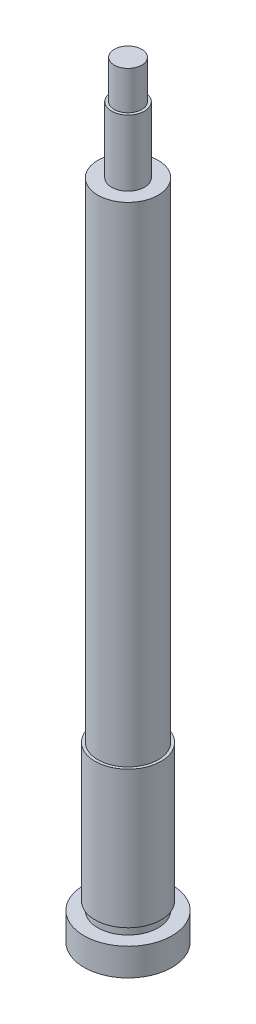
SolidWorks part; units mm, degrees
ref_plane "Front Plane" through (0, 0, 0) normal (0, 0, 1) x (1, 0, 0)
ref_plane "Top Plane" through (0, 0, 0) normal (0, 1, 0) x (1, 0, 0)
ref_plane "Right Plane" through (0, 0, 0) normal (1, 0, 0) x (0, 0, -1)
sketch "Sketch1" plane through (0, 0, 0) normal (0, 0, 1) x (1, 0, 0)
  line L0 (0, 0) -> (0, 279) construction
  line L1 (0, 0) -> (-16, 0)
  line L2 (-16, 0) -> (-16, 10)
  line L3 (0, 0) -> (0, 279)
  line L4 (-11, 63) -> (-11, 241)
  line L5 (-11, 10) -> (-16, 10)
  line L6 (-11, 13) -> (-12, 13)
  line L7 (-12, 13) -> (-12, 63)
  line L8 (-11, 10) -> (-11, 13)
  line L9 (-11, 63) -> (-12, 63)
  line L10 (-6, 241) -> (-11, 241)
  line L11 (-6, 241) -> (-6, 265)
  line L12 (-5, 265) -> (-6, 265)
  line L13 (-5, 265) -> (-5, 279)
  line L14 (-5, 279) -> (0, 279)
  dimension "D4" = 10
  dimension "D1" = 279
  dimension "D2" = 16
  dimension "D3" = 12
  dimension "D5" = 13
  dimension "D6" = 63
  dimension "D7" = 241
  dimension "D8" = 265
revolve "Revolve1" add sketch "Sketch1" angle 360 about L0
cosmetic thread "Cosmetic Thread2" parameters "D1"=5, "D2"=21.797
cosmetic thread "Cosmetic Thread3" parameters "D1"=5, "D2"=8.891
